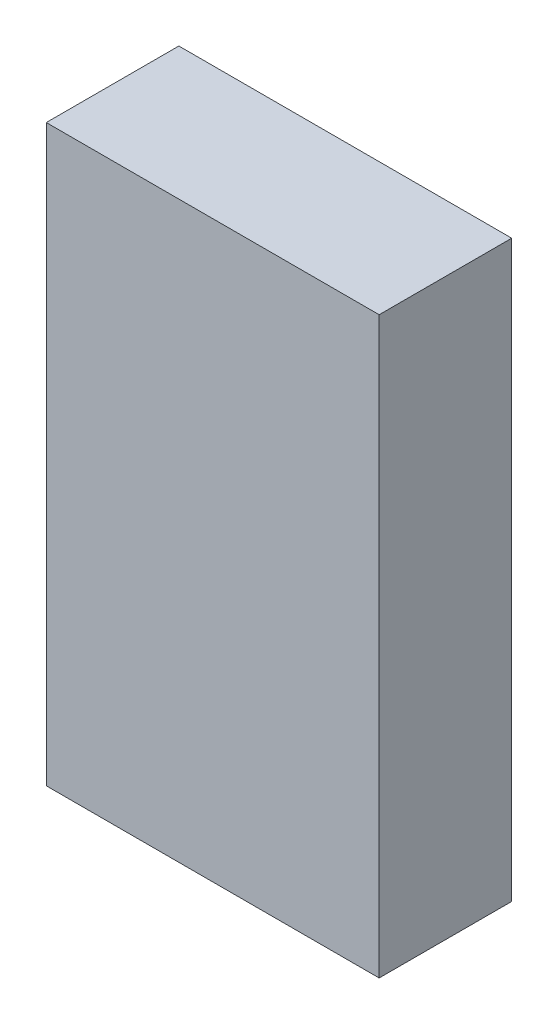
SolidWorks part; units mm, degrees
ref_plane "Спереди" through (0, 0, 0) normal (0, 0, 1) x (1, 0, 0)
ref_plane "Сверху" through (0, 0, 0) normal (0, 1, 0) x (1, 0, 0)
ref_plane "Справа" through (0, 0, 0) normal (1, 0, 0) x (0, 0, -1)
sketch "Эскиз1" plane through (0, 0, 0) normal (0, 0, 1) x (1, 0, 0)
  line L1 (-565, 975) -> (565, 975)
  line L2 (-565, 975) -> (-565, -975)
  line L3 (-565, -975) -> (565, -975)
  line L4 (565, 975) -> (565, -975)
  line L5 (-565, 975) -> (565, -975) construction
  line L6 (-565, -975) -> (565, 975) construction
  point P0 (0, 0)
extrude "Бобышка-Вытянуть1" add sketch "Эскиз1" along normal blind 450
sketch "Эскиз2" plane through (0, 0, 450) normal (0, 0, 1) x (1, 0, 0)
  line L0 (0, 975) -> (0, -975)
  line L1 (39.8609, 0) -> (143.924, 0) construction
  line L2 (39.8609, 15.5859) -> (143.924, 15.5859)
  line L3 (39.8609, -15.5859) -> (143.924, -15.5859)
  arc A0 (39.8609, 15.5859) -> (39.8609, -15.5859) centre (39.8609, 0) ccw
  arc A1 (143.924, -15.5859) -> (143.924, 15.5859) centre (143.924, 0) ccw
  text T0 "НТВ" font "Arial" height 80
  point P6 (91.8924, 0)
